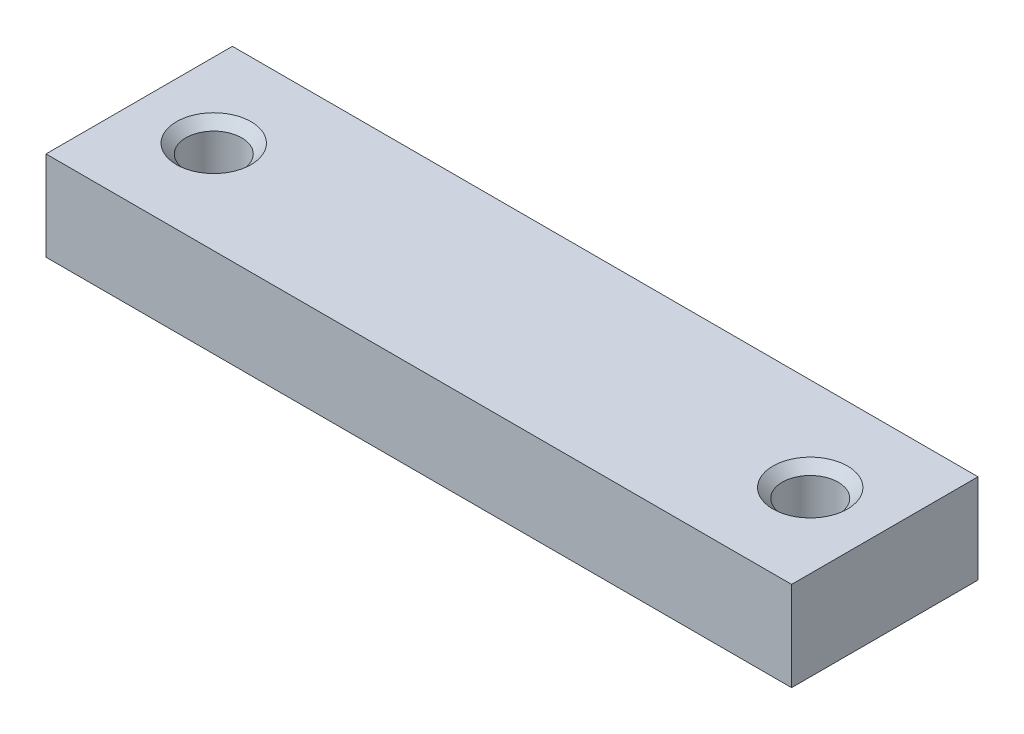
SolidWorks part; units mm, degrees
material "Сталь 08пс ГОСТ 535-88"
ref_plane "Спереди" through (0, 0, 0) normal (0, 0, 1) x (1, 0, 0)
ref_plane "Сверху" through (0, 0, 0) normal (0, 1, 0) x (1, 0, 0)
ref_plane "Справа" through (0, 0, 0) normal (1, 0, 0) x (0, 0, -1)
sketch "Эскиз1" plane through (0, 0, 0) normal (0, 0, 1) x (1, 0, 0)
  line L0 (-34.4035, 28.782) -> (34.4035, -28.782) construction
  line L1 (-34.4035, 28.782) -> (34.4035, 28.782)
  line L2 (-34.4035, 28.782) -> (-34.4035, -28.782)
  line L3 (-34.4035, -28.782) -> (34.4035, -28.782)
  line L4 (34.4035, 28.782) -> (34.4035, -28.782)
sketch "Эскиз2" plane through (0, 0, 0) normal (0, 1, 0) x (1, 0, 0)
  line L1 (-50, 12.5) -> (50, 12.5)
  line L2 (-50, 12.5) -> (-50, -12.5)
  line L3 (-50, -12.5) -> (50, -12.5)
  line L4 (50, 12.5) -> (50, -12.5)
  line L5 (-50, 12.5) -> (50, -12.5) construction
  line L6 (-50, -12.5) -> (50, 12.5) construction
  point P0 (0, 0)
  dimension "D1" = 25
  dimension "D2" = 100
extrude "Бобышка-Вытянуть1" add sketch "Эскиз2" along normal mid plane 12
sketch "Эскиз3" plane through (0, 6, 0) normal (0, 1, 0) x (1, 0, 0)
  line L0 (0, 7.288) -> (0, -7.288) construction
  line L1 (-12.0761, 0) -> (14.8727, 0) construction
  circle A0 centre (-40, 0) radius 3.75
  circle A1 centre (40, 0) radius 3.75
  dimension "D2" = 7.5
  dimension "D1" = 80
extrude "Вырез-Вытянуть1" cut sketch "Эскиз3" against normal up to next
chamfer "Фаска2" distance 1.25 angle 45 2 edges at (40, 6, 3.75) (-40, 6, 3.75)
